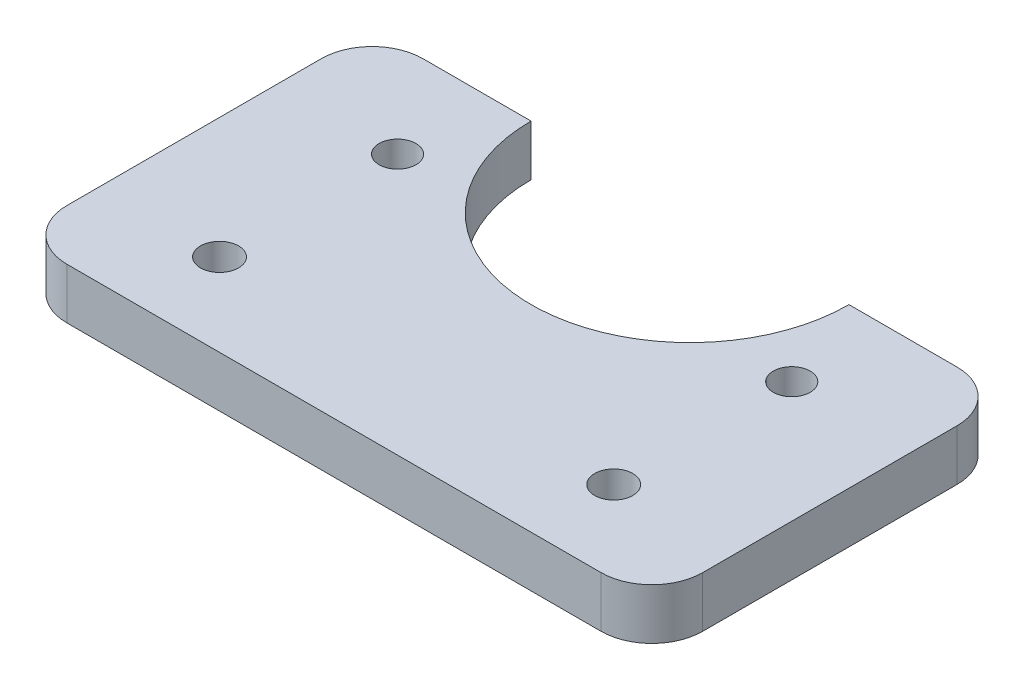
SolidWorks part; units mm, degrees
ref_plane "前视基准面" through (0, 0, 0) normal (0, 0, 1) x (1, 0, 0)
ref_plane "上视基准面" through (0, 0, 0) normal (0, 1, 0) x (1, 0, 0)
ref_plane "右视基准面" through (0, 0, 0) normal (1, 0, 0) x (0, 0, -1)
other "Configuration Table"
sketch "草图1" plane through (0, 0, 0) normal (0, 1, 0) x (1, 0, 0)
  line L1 (-25, 12.5) -> (25, 12.5)
  line L2 (-25, 12.5) -> (-25, -12.5)
  line L3 (-25, -12.5) -> (25, -12.5)
  line L4 (25, 12.5) -> (25, -12.5)
  line L5 (-25, 12.5) -> (25, -12.5) construction
  line L6 (-25, -12.5) -> (25, 12.5) construction
  point P0 (0, 0)
  dimension "D1" = 50
  dimension "D2" = 25
extrude "凸台-拉伸1" add sketch "草图1" along normal blind 4
sketch "草图2" plane through (0, 4, 0) normal (0, 1, 0) x (1, 0, 0)
  line L0 (-25, 12.5) -> (-25, 5) construction
  line L1 (-25, 12.5) -> (-25, -12.5) construction
  line L2 (-25, 5) -> (-15.5, 5) construction
  line L3 (-15.5, 5) -> (15.5, 5) construction
  circle A0 centre (-15.5, 5) radius 1.45
  circle A1 centre (15.5, 5) radius 1.45
  dimension "D3" = 2.9
  dimension "D5" = 2.9
  dimension "D1" = 7.5
  dimension "D2" = 9.5
  dimension "D4" = 31
extrude "切除-拉伸1" cut sketch "草图2" against normal blind 4
sketch "草图3" plane through (0, 4, 0) normal (0, 1, 0) x (1, 0, 0)
  line L0 (25, 12.5) -> (-25, 12.5) construction
  circle A0 centre (0, 12.5) radius 12.5
  dimension "D1" = 25
extrude "切除-拉伸2" cut sketch "草图3" against normal blind 4
extrude "切除-拉伸3" cut sketch "草图4" against normal blind 8
sketch "草图4" [suppressed] plane through (149.8259, 4, -52.4808) normal (0, 1, 0) x (1, 0, 0.0035)
  line L0 (-165.1605, -48.0531) -> (-165.1605, -63.0531) construction
  line L1 (-165.1605, -63.0531) -> (-134.1605, -63.0531) construction
  circle A1 centre (-134.1605, -63.0531) radius 2.25
  circle A2 centre (-165.1605, -63.0531) radius 2.25
sketch "草图5" plane through (0, 0, 12.5) normal (0, 0, 1) x (1, 0, 0)
  line L4 (-25, 0) -> (25, 0)
  line L5 (25, 0) -> (25, 4)
  line L6 (25, 4) -> (-25, 4)
  line L7 (-25, 4) -> (-25, 0)
  line L8 (-25, 0) -> (25, 0)
  line L9 (25, 0) -> (25, 4)
  line L10 (25, 4) -> (-25, 4)
  line L11 (-25, 4) -> (-25, 0)
  dimension "D1" = 0
extrude "凸台-拉伸2" add sketch "草图5" along normal blind 3
sketch "草图6" [suppressed] plane through (0, 0, 0) normal (0, -1, 0) x (1, 0, 0)
  line L5 (-25, -12.5) -> (-12.5, -12.5)
  line L6 (12.5, -12.5) -> (25, -12.5)
  line L7 (25, -12.5) -> (25, 15.5)
  line L8 (25, 15.5) -> (-25, 15.5)
  line L9 (-25, 15.5) -> (-25, -12.5)
  line L10 (-25, -12.5) -> (-12.5, -12.5)
  line L11 (12.5, -12.5) -> (25, -12.5)
  line L12 (25, -12.5) -> (25, 15.5)
  line L13 (25, 15.5) -> (-25, 15.5)
  line L14 (-25, 15.5) -> (-25, -12.5)
  circle A0 centre (-15.5, -5) radius 1.45 construction
  arc A1 (12.5, -12.5) -> (-12.5, -12.5) centre (0, -12.5) ccw
  arc A2 (12.5, -12.5) -> (-12.5, -12.5) centre (0, -12.5) ccw
  circle A3 centre (15.5, -5) radius 1.45 construction
  circle A4 centre (15.4479, 10.1073) radius 2.25 construction
  circle A5 centre (-15.552, 9.9999) radius 2.25 construction
  circle A6 centre (-15.5, -5) radius 1.45
  circle A7 centre (15.5, -5) radius 1.45
  circle A8 centre (15.4479, 10.1073) radius 2.25
  circle A9 centre (-15.552, 9.9999) radius 2.25
  dimension "D1" = 0
extrude "凸台-拉伸3" [suppressed] add sketch "草图6" along normal blind 1
fillet "圆角1" radius 4 4 edges at (-25, 2, -12.5) (25, 2, -12.5) (25, 2, 15.5) (-25, 2, 15.5)
fillet "圆角2" [suppressed] radius 4
sketch "草图7" [suppressed] plane through (0, 4, 0) normal (0, 1, 0) x (1, 0, 0)
  line L1 (-15.552, -9.9999) -> (15.4479, -10.1073)
  circle A0 centre (-15.552, -9.9999) radius 2.25
  circle A1 centre (-15.552, -9.9999) radius 1.45
  circle A4 centre (15.4479, -10.1073) radius 2.25
  circle A5 centre (15.4479, -10.1073) radius 1.45
  dimension "D1" = 2.9
  dimension "D2" = 2.9
extrude "凸台-拉伸4" [suppressed] add sketch "草图7" against normal up to surface (5 mm away)
sketch "草图11" plane through (0, 4, 0) normal (0, 1, 0) x (1, 0, 0)
  line L0 (-15.5, 5) -> (-15.5, -9) construction
  line L1 (15.5, 5) -> (15.5, -9) construction
  circle A0 centre (-15.5, -9) radius 1.5
  circle A1 centre (15.5, -9) radius 1.5
  dimension "D2" = 3
  dimension "D3" = 3
  dimension "D1" = 14
  dimension "D4" = 14
extrude "切除-拉伸4" cut sketch "草图11" against normal blind 10
